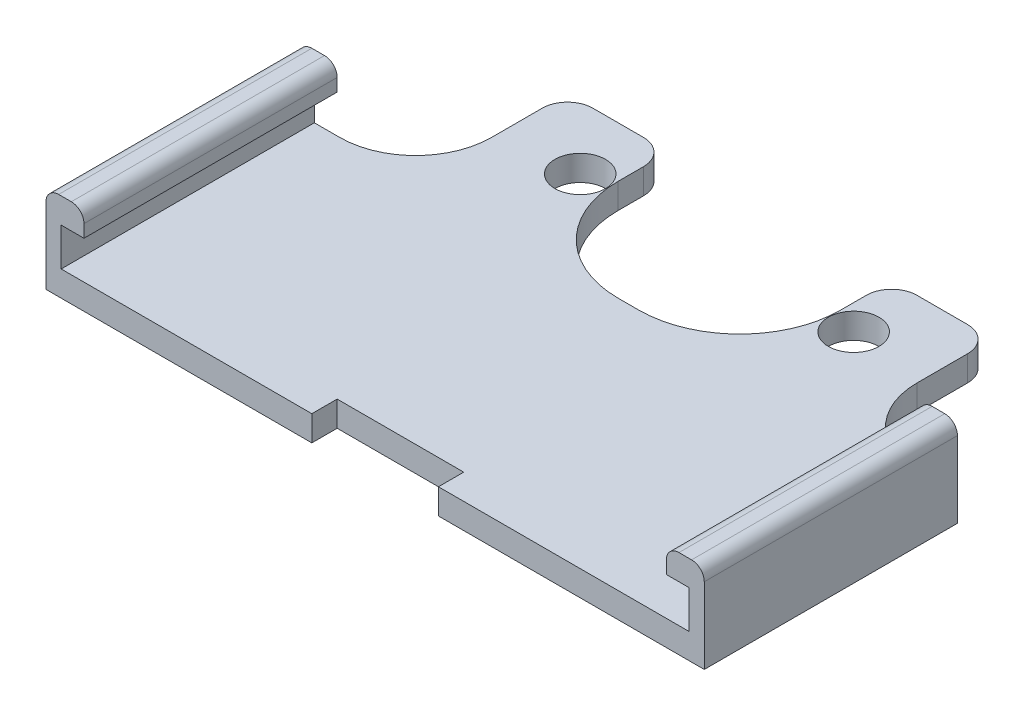
SolidWorks part; units mm, degrees
ref_plane "Спереди" through (0, 0, 0) normal (0, 0, 1) x (1, 0, 0)
ref_plane "Сверху" through (0, 0, 0) normal (0, 1, 0) x (1, 0, 0)
ref_plane "Справа" through (0, 0, 0) normal (1, 0, 0) x (0, 0, -1)
sketch "Эскиз1" plane through (0, 0, 0) normal (0, 1, 0) x (1, 0, 0)
  line L0 (-7.4, 16) -> (-5.4, 16)
  line L1 (-4.4, 15) -> (-4.4, 14)
  line L2 (-0.4, 10) -> (0.4, 10)
  line L3 (4.4, 14) -> (4.4, 15)
  line L4 (5.4, 16) -> (7.4, 16)
  line L5 (8.4, 15) -> (8.4, 13)
  line L6 (11.4, 10) -> (13, 10)
  line L7 (13, 10) -> (13, 0)
  line L8 (13, 0) -> (-13, 0)
  line L9 (-13, 0) -> (-13, 10)
  line L10 (-13, 10) -> (-11.4, 10)
  line L11 (-8.4, 13) -> (-8.4, 15)
  arc A6 (5.4, 16) -> (4.4, 15) centre (5.4, 15) ccw
  arc A7 (-5.4, 16) -> (-4.4, 15) centre (-5.4, 15) cw
  arc A8 (7.4, 16) -> (8.4, 15) centre (7.4, 15) cw
  arc A9 (-7.4, 16) -> (-8.4, 15) centre (-7.4, 15) ccw
  arc A10 (0.4, 10) -> (4.4, 14) centre (0.4, 14) ccw
  arc A11 (-0.4, 10) -> (-4.4, 14) centre (-0.4, 14) cw
  arc A12 (8.4, 13) -> (11.4, 10) centre (11.4, 13) ccw
  arc A13 (-11.4, 10) -> (-8.4, 13) centre (-11.4, 13) ccw
  point P13 (0, 0)
  point P18 (4.4, 10)
  point P21 (-4.4, 10)
  point P34 (8.4, 10)
  point P37 (-8.4, 10)
  dimension "D6" = 4
  dimension "D7" = 4
  dimension "D3" = 1
  dimension "D2" = 6
  dimension "D8" = 3
  dimension "D1" = 8.8
  dimension "D5" = 10
  dimension "D9" = 26
extrude "Бобышка-Вытянуть1" add sketch "Эскиз1" against normal blind 1 contours L10 A13 L11 A9 L0 A7 L1 A11 L2 A10 L3 A6 L4 A8 L5 A12 L6 L7 L8 L9
sketch "Эскиз3" plane through (0, 0, 0) normal (0, 1, 0) x (1, 0, 0)
  line L2 (-4.4, 15) -> (-4.4, 14) construction
  line L3 (4.4, 14) -> (4.4, 15) construction
  line L4 (-0.4, 10) -> (0.4, 10) construction
  circle A0 centre (-5.4, 13.5) radius 1
  circle A1 centre (5.4, 13.5) radius 1
  point P6 (0, 10)
  dimension "D1" = 2
  dimension "D2" = 2
  dimension "D3" = 3.5
  dimension "D4" = 3.5
  dimension "D5" = 1
  dimension "D6" = 1
extrude "Вырез-Вытянуть3" cut sketch "Эскиз3" against normal through all
sketch "Эскиз6" plane through (0, 0, 0) normal (0, 1, 0) x (1, 0, 0)
  line L1 (-2.5, 1) -> (2.5, 1)
  line L2 (-2.5, 1) -> (-2.5, -1)
  line L3 (-2.5, -1) -> (2.5, -1)
  line L4 (2.5, 1) -> (2.5, -1)
  line L5 (-2.5, 1) -> (2.5, -1) construction
  line L6 (-2.5, -1) -> (2.5, 1) construction
  point P0 (0, 0)
  dimension "D1" = 2
  dimension "D2" = 5
extrude "Вырез-Вытянуть4" cut sketch "Эскиз6" against normal through all
sketch "Эскиз7" plane through (0, 0, 0) normal (0, 1, 0) x (1, 0, 0)
  line L0 (-13, 0) -> (-13, 10) construction
  line L1 (-13, 10) -> (-12.4, 10)
  line L2 (-13, 10) -> (-13, 0)
  line L3 (-13, 0) -> (-12.4, 0)
  line L4 (-12.4, 10) -> (-12.4, 0)
  line L6 (13, 10) -> (12.4, 10)
  line L7 (13, 10) -> (13, 0)
  line L8 (13, 0) -> (12.4, 0)
  line L9 (12.4, 10) -> (12.4, 0)
  line L12 (13, 10) -> (13, 0) construction
  point P4 (-12.4, 5)
  point P5 (-13, 5)
  point P10 (13, 5)
  point P12 (0, 0)
  point P14 (13, 5)
  point P17 (-13, 5)
  dimension "D1" = 0.6
  dimension "D2" = 0.6
  dimension "D3" = 10
  dimension "D4" = 10
extrude "Бобышка-Вытянуть2" add sketch "Эскиз7" along normal blind 1.5
sketch "Эскиз8" plane through (0, 1.5, 0) normal (0, 1, 0) x (1, 0, 0)
  line L1 (-13, 10) -> (-11.5, 10)
  line L2 (-13, 10) -> (-13, 0)
  line L3 (-13, 0) -> (-11.5, 0)
  line L4 (-11.5, 10) -> (-11.5, 0)
  line L5 (13, 10) -> (11.5, 10)
  line L6 (13, 10) -> (13, 0)
  line L7 (13, 0) -> (11.5, 0)
  line L8 (11.5, 10) -> (11.5, 0)
  dimension "D1" = 10
  dimension "D2" = 10
  dimension "D3" = 1.5
  dimension "D4" = 1.5
extrude "Бобышка-Вытянуть3" add sketch "Эскиз8" along normal blind 1
fillet "Скругление1" radius 0.5 4 edges at (13, 2.5, -5) (-13, 2.5, -5) (11.5, 2.5, -5) (-11.5, 2.5, -5)
